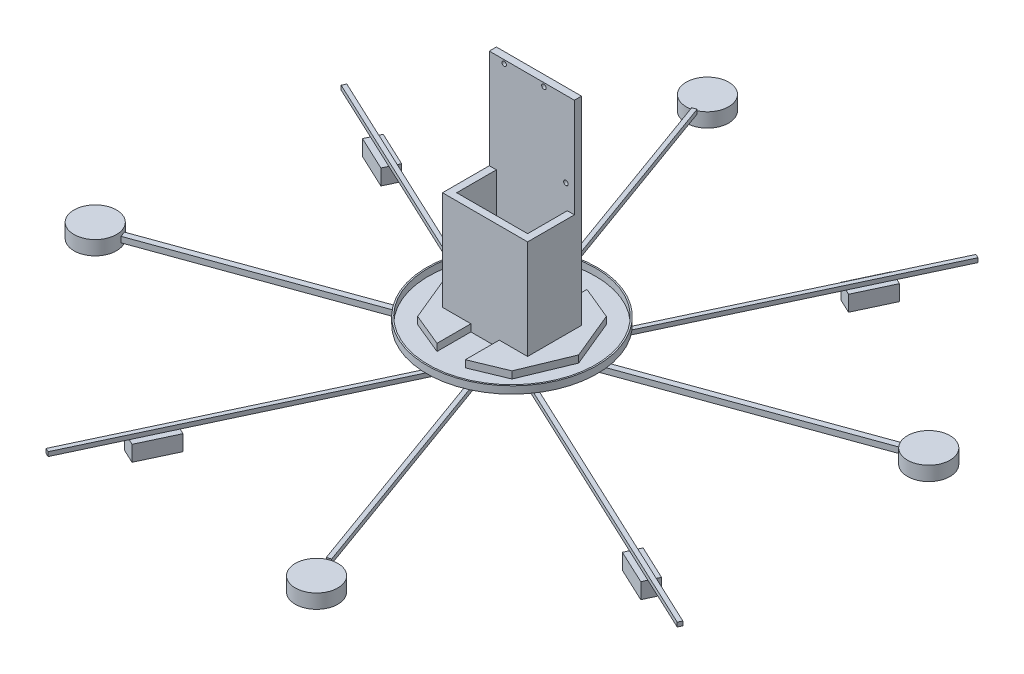
SolidWorks part; units mm, degrees
material "Pieza"
ref_plane "Alzado" through (0, 0, 0) normal (0, 0, 1) x (1, 0, 0)
ref_plane "Planta" through (0, 0, 0) normal (0, 1, 0) x (1, 0, 0)
ref_plane "Vista lateral" through (0, 0, 0) normal (1, 0, 0) x (0, 0, -1)
sketch "Croquis1" plane through (0, 0, 0) normal (0, 1, 0) x (1, 0, 0)
  line L0 (-28, 17) -> (-28, -17)
  line L1 (47.0363, 0) -> (33.2597, 33.2597)
  line L2 (33.2597, 33.2597) -> (0, 47.0363)
  line L3 (0, 47.0363) -> (-33.2597, 33.2597)
  line L4 (-33.2597, 33.2597) -> (-47.0363, 0)
  line L5 (-47.0363, 0) -> (-33.2597, -33.2597)
  line L6 (-33.2597, -33.2597) -> (0, -47.0363)
  line L7 (0, -47.0363) -> (33.2597, -33.2597)
  line L8 (33.2597, -33.2597) -> (47.0363, 0)
  line L9 (-25, 14) -> (25, 14)
  line L10 (-25, 14) -> (-25, -14)
  line L11 (-25, -14) -> (25, -14)
  line L12 (25, 14) -> (25, -14)
  line L13 (-25, 14) -> (25, -14) construction
  line L14 (-25, -14) -> (25, 14) construction
  line L15 (-28, -17) -> (28, -17)
  line L16 (28, 17) -> (28, -17)
  line L17 (-28, 17) -> (28, 17)
  circle A0 centre (0, 0) radius 43.4558 construction
  dimension "D1" = 36
  dimension "D2" = 50
  dimension "D3" = 28
  dimension "D4" = 3
extrude "Saliente-Extruir1" add sketch "Croquis1" along normal blind 5 contours L7 L8 L1 L2 L3 L4 L5 L6 L0 L17 L16 L15 | L17 L0 L15 L16 L9 L12 L11 L10 | L12 L9 L10 L11
sketch "Croquis2" plane through (0, 5, 0) normal (0, 1, 0) x (1, 0, 0)
  line L0 (30, 19) -> (-30, 19)
  line L1 (-30, 19) -> (-30, -19)
  line L2 (-30, -19) -> (30, -19)
  line L3 (30, -19) -> (30, 19)
  line L4 (25, 14) -> (-25, 14)
  line L5 (25, -14) -> (25, 14)
  line L6 (-25, -14) -> (25, -14)
  line L7 (-25, 14) -> (-25, -14)
  line L24 (25, 14) -> (-25, 14)
  line L25 (25, -14) -> (25, 14)
  line L26 (-25, -14) -> (25, -14)
  line L27 (-25, 14) -> (-25, -14)
  dimension "D1" = 5
  dimension "D2" = 0
extrude "Saliente-Extruir2" add sketch "Croquis2" along normal blind 70
sketch "Croquis4" plane through (0, 75, 0) normal (0, 1, 0) x (1, 0, 0)
  line L0 (30, 14) -> (-30, 14)
  line L1 (-30, 19) -> (-30, 14)
  line L2 (30, 19) -> (30, 14)
  line L4 (-30, -19) -> (30, -19)
  line L5 (30, -19) -> (30, 19)
  line L6 (30, 19) -> (-30, 19)
  line L7 (-30, 19) -> (-30, -19)
  line L8 (-30, -19) -> (30, -19) construction
  line L9 (30, -19) -> (30, 19) construction
  line L10 (30, 19) -> (-30, 19)
  line L11 (-30, 19) -> (-30, -19) construction
  dimension "D2" = 5
  dimension "D1" = 0
extrude "Saliente-Extruir4" add sketch "Croquis4" along normal blind 70
sketch "Croquis5" plane through (0, 0, -14) normal (0, 0, 1) x (1, 0, 0)
  line L0 (0, 0) -> (0, 145) construction
  line L1 (-30, 145) -> (30, 145) construction
  line L3 (-26.5, 145) -> (26.5, 145)
  line L4 (-26.5, 145) -> (-26.5, 77)
  line L5 (-26.5, 77) -> (26.5, 77)
  line L6 (26.5, 145) -> (26.5, 77)
  line L7 (-26.5, 145) -> (26.5, 77) construction
  line L8 (-26.5, 77) -> (26.5, 145) construction
  circle A0 centre (-8.5, 142.5) radius 1.59
  circle A1 centre (19.5, 142.5) radius 1.59
  circle A2 centre (-24, 91.5) radius 1.59
  circle A3 centre (-19.5, 142.5) radius 1.59
  circle A4 centre (8.5, 142.5) radius 1.59
  circle A5 centre (24, 91.5) radius 1.59
  point P6 (0, 111)
  point P11 (19.5, 142.5)
  point P12 (-8.5, 142.5)
  point P17 (-24, 91.5)
  dimension "D7" = 3.18
  dimension "D8" = 3.18
  dimension "D11" = 3.18
  dimension "D1" = 53
  dimension "D2" = 68
  dimension "D3" = 65.5
  dimension "D4" = 7
  dimension "D5" = 65.5
  dimension "D6" = 35
  dimension "D9" = 50.5
  dimension "D10" = 14.5
extrude "Cortar-Extruir1" cut sketch "Croquis5" against normal through all contours A3 | A5 | A4
sketch "Croquis6" plane through (0, 5, 0) normal (0, 1, 0) x (1, 0, 0)
  line L0 (0, 47.0363) -> (0, -47.0363) construction
  line L1 (-47.0363, 0) -> (47.0363, 0) construction
  line L2 (30, 19) -> (-30, 19) construction
  line L3 (-10, 49) -> (10, 49)
  line L4 (-10, 49) -> (-10, 19)
  line L5 (-10, 19) -> (10, 19)
  line L6 (10, 49) -> (10, 19)
  line L7 (-10, 49) -> (10, 19) construction
  line L8 (-10, 19) -> (10, 49) construction
  line L9 (-10, -19) -> (10, -19)
  line L10 (10, -49) -> (10, -19)
  line L11 (-10, -49) -> (10, -49)
  line L12 (-10, -49) -> (-10, -19)
  point P8 (0, 34)
  dimension "D1" = 20
  dimension "D2" = 30
extrude "Cortar-Extruir2" cut sketch "Croquis6" against normal through all
sketch "Croquis7" plane through (0, 0, 0) normal (0, -1, 0) x (1, 0, 0)
  circle A0 centre (0, 0) radius 60
  dimension "D1" = 120
extrude "Saliente-Extruir5" add sketch "Croquis7" along normal blind 0.1
sketch "Croquis9" plane through (0, 0, 0) normal (0, 0, 1) x (1, 0, 0)
  line L0 (59, 0) -> (60, 0)
  line L1 (60, 0) -> (-60, 0) construction
  line L2 (60, 0) -> (60, 5)
  line L3 (60, 5) -> (59, 5)
  line L4 (59, 5) -> (59, 0)
  line L5 (60, -0.1) -> (60, 0) construction
  line L6 (0, 0) -> (0, 108.5926) construction
  dimension "D1" = 1
  dimension "D2" = 5
revolve "Revolución1" add sketch "Croquis9" angle 360 about L6
sketch "Croquis10" plane through (0, -0.1, 0) normal (0, -1, 0) x (1, 0, 0)
  line L7 (-21.9638, 41.9554) -> (-45.1977, 14.1362)
  line L8 (-45.1977, 14.1362) -> (-41.9554, -21.9638)
  line L9 (-41.9554, -21.9638) -> (-14.1362, -45.1977)
  line L10 (-14.1362, -45.1977) -> (21.9638, -41.9554)
  line L11 (21.9638, -41.9554) -> (45.1977, -14.1362)
  line L12 (45.1977, -14.1362) -> (41.9554, 21.9638)
  line L13 (41.9554, 21.9638) -> (14.1362, 45.1977)
  line L14 (14.1362, 45.1977) -> (-21.9638, 41.9554)
  circle A0 centre (0, 0) radius 43.752 construction
  dimension "D1" = 36.1
extrude "Saliente-Extruir6" add sketch "Croquis10" along normal blind 0.2
sketch "Croquis11" plane through (0, -0.3, 0) normal (0, -1, 0) x (1, 0, 0)
  line L1 (-18.9219, -0.8699) -> (-12.7647, -13.9949)
  line L2 (-12.7647, -13.9949) -> (0.8699, -18.9219)
  line L3 (0.8699, -18.9219) -> (13.9949, -12.7647)
  line L4 (13.9949, -12.7647) -> (18.9219, 0.8699)
  line L5 (18.9219, 0.8699) -> (12.7647, 13.9949)
  line L6 (12.7647, 13.9949) -> (-0.8699, 18.9219)
  line L7 (-0.8699, 18.9219) -> (-13.9949, 12.7647)
  line L8 (-13.9949, 12.7647) -> (-18.9219, -0.8699)
  circle A0 centre (0, 0) radius 17.5 construction
  dimension "D2" = 17.5
extrude "Saliente-Extruir7" add sketch "Croquis11" along normal blind 22.1
sketch "Croquis12" plane through (5.9474, 0, 16.4584) normal (0.3399, 0, 0.9405) x (0.9405, 0, -0.3399)
  line L0 (7.2487, -22.4) -> (-7.2487, -22.4) construction
  line L1 (-1.6681, -5.4) -> (1.3319, -5.4)
  line L2 (-1.6681, -5.4) -> (-1.6681, -8.4)
  line L3 (-1.6681, -8.4) -> (1.3319, -8.4)
  line L4 (1.3319, -5.4) -> (1.3319, -8.4)
  dimension "D1" = 14
  dimension "D2" = 3
extrude "Saliente-Extruir8" add sketch "Croquis12" along normal blind 197
sketch "Croquis13" plane through (-5.9474, 0, -16.4584) normal (-0.3399, 0, -0.9405) x (-0.9405, 0, 0.3399)
  line L0 (-1.3319, -5.4) -> (1.6681, -5.4) construction
  line L1 (1.6681, -5.4) -> (1.6681, -8.4) construction
  line L2 (1.6681, -8.4) -> (-1.3319, -8.4) construction
  line L3 (-1.3319, -8.4) -> (-1.3319, -5.4) construction
  line L4 (-1.3319, -5.4) -> (1.6681, -5.4)
  line L5 (1.6681, -5.4) -> (1.6681, -8.4)
  line L6 (1.6681, -8.4) -> (-1.3319, -8.4)
  line L7 (-1.3319, -8.4) -> (-1.3319, -5.4)
extrude "Saliente-Extruir9" add sketch "Croquis13" along normal blind 197
sketch "Croquis14" plane through (-16.4584, 0, 5.9474) normal (-0.9405, 0, 0.3399) x (0.3399, 0, 0.9405)
  line L0 (7.2487, -22.4) -> (-7.2487, -22.4) construction
  line L1 (-2.2487, -9.4) -> (1.7513, -9.4)
  line L2 (-2.2487, -9.4) -> (-2.2487, -13.4)
  line L3 (-2.2487, -13.4) -> (1.7513, -13.4)
  line L4 (1.7513, -9.4) -> (1.7513, -13.4)
  line L5 (-7.2487, -22.4) -> (-7.2487, -0.3) construction
  dimension "D1" = 9
  dimension "D2" = 4
  dimension "D3" = 4
  dimension "D4" = 5
extrude "Saliente-Extruir10" add sketch "Croquis14" along normal blind 197
sketch "Croquis15" plane through (16.4584, 0, -5.9474) normal (0.9405, 0, -0.3399) x (-0.3399, 0, -0.9405)
  line L0 (2.2487, -9.4) -> (2.2487, -13.4) construction
  line L1 (2.2487, -13.4) -> (-1.7513, -13.4) construction
  line L2 (-1.7513, -9.4) -> (2.2487, -9.4) construction
  line L3 (-1.7513, -13.4) -> (-1.7513, -9.4) construction
  line L12 (2.2487, -9.4) -> (2.2487, -13.4)
  line L13 (2.2487, -13.4) -> (-1.7513, -13.4)
  line L14 (-1.7513, -9.4) -> (2.2487, -9.4)
  line L15 (-1.7513, -13.4) -> (-1.7513, -9.4)
extrude "Saliente-Extruir12" add sketch "Croquis15" along normal blind 197 contours L14 L12 L13 L15
ref_plane "Plano1" through (0, -6.4, 0) normal (0, 1, 0) x (1, 0, 0)
sketch "Croquis17" plane through (0, -6.4, 0) normal (0, 1, 0) x (1, 0, 0)
  line L0 (-201.1377, -74.545) -> (-202.4971, -70.7831) construction
  line L1 (104.0732, -288.0051) -> (-104.0732, 288.0051) construction
  circle A0 centre (-215.8297, -78.0242) radius 15
  circle A1 centre (-78.0242, 215.8297) radius 15
  circle A2 centre (215.8297, 78.0242) radius 15
  circle A3 centre (78.0242, -215.8297) radius 15
  point P8 (0, 0)
  point P17 (0, 0)
  dimension "D1" = 4
  dimension "D2" = 30
extrude "Saliente-Extruir13" add sketch "Croquis17" against normal blind 10 separate body
sketch "Croquis18" plane through (7.4324, 0, -15.8433) normal (0.4247, 0, -0.9053) x (-0.9053, 0, -0.4247)
  line L0 (7.2487, -22.4) -> (-7.2487, -22.4) construction
  line L1 (1.5, -20.4) -> (-1.5, -20.4)
  line L2 (1.5, -20.4) -> (1.5, -17.4)
  line L3 (1.5, -17.4) -> (-1.5, -17.4)
  line L4 (-1.5, -20.4) -> (-1.5, -17.4)
  line L5 (1.5, -20.4) -> (-1.5, -17.4) construction
  line L6 (1.5, -17.4) -> (-1.5, -20.4) construction
  point P0 (0, -18.9)
  point P7 (0, -22.4)
  dimension "D1" = 2
  dimension "D2" = 3
  dimension "D3" = 3
extrude "Saliente-Extruir14" add sketch "Croquis18" along normal blind 229
sketch "Croquis19" plane through (-7.4324, 0, 15.8433) normal (-0.4247, 0, 0.9053) x (0.9053, 0, 0.4247)
  line L0 (1.5, -20.4) -> (-1.5, -20.4) construction
  line L1 (1.5, -17.4) -> (1.5, -20.4) construction
  line L2 (-1.5, -17.4) -> (1.5, -17.4) construction
  line L3 (-1.5, -20.4) -> (-1.5, -17.4) construction
  line L12 (1.5, -20.4) -> (-1.5, -20.4)
  line L13 (1.5, -17.4) -> (1.5, -20.4)
  line L14 (-1.5, -17.4) -> (1.5, -17.4)
  line L15 (-1.5, -20.4) -> (-1.5, -17.4)
extrude "Saliente-Extruir15" add sketch "Croquis19" along normal blind 229
sketch "Croquis20" plane through (15.8433, 0, 7.4324) normal (0.9053, 0, 0.4247) x (0.4247, 0, -0.9053)
  line L0 (7.2487, -22.4) -> (-7.2487, -22.4) construction
  line L2 (1.5, -20.4) -> (-1.5, -20.4)
  line L3 (1.5, -20.4) -> (1.5, -17.4)
  line L4 (1.5, -17.4) -> (-1.5, -17.4)
  line L5 (-1.5, -20.4) -> (-1.5, -17.4)
  line L6 (1.5, -20.4) -> (-1.5, -17.4) construction
  line L7 (1.5, -17.4) -> (-1.5, -20.4) construction
  point P0 (0, -22.4)
  point P1 (0, -18.9)
  dimension "D1" = 2
  dimension "D2" = 3
  dimension "D3" = 3
extrude "Saliente-Extruir16" add sketch "Croquis20" along normal blind 229
sketch "Croquis21" plane through (-15.8433, 0, -7.4324) normal (-0.9053, 0, -0.4247) x (-0.4247, 0, 0.9053)
  line L0 (1.5, -17.4) -> (1.5, -20.4) construction
  line L1 (-1.5, -17.4) -> (1.5, -17.4) construction
  line L2 (1.5, -20.4) -> (-1.5, -20.4) construction
  line L3 (-1.5, -20.4) -> (-1.5, -17.4) construction
  line L4 (1.5, -17.4) -> (1.5, -20.4)
  line L5 (-1.5, -17.4) -> (1.5, -17.4)
  line L6 (1.5, -20.4) -> (-1.5, -20.4)
  line L7 (-1.5, -20.4) -> (-1.5, -17.4)
extrude "Saliente-Extruir17" add sketch "Croquis21" along normal blind 229
sketch "Croquis22" plane through (0, -20.4, 0) normal (0, -1, 0) x (1, 0, 0)
  line L0 (106.0487, -222.5268) -> (103.3327, -223.8009) construction
  line L7 (91.1998, -181.9962) -> (81.2412, -186.668)
  line L11 (81.2412, -186.668) -> (69.774, -162.2241)
  line L12 (69.774, -162.2241) -> (79.7327, -157.5523)
  line L14 (79.7327, -157.5523) -> (91.1998, -181.9962)
  line L15 (106.0487, -222.5268) -> (8.7904, -15.2062) construction
  line L16 (103.3327, -223.8009) -> (6.0744, -16.4803) construction
  line L17 (149.0238, 412.3982) -> (-149.0238, -412.3982) construction
  line L18 (-157.5523, -79.7327) -> (-181.9962, -91.1998)
  line L19 (-181.9962, -91.1998) -> (-186.668, -81.2412)
  line L20 (-186.668, -81.2412) -> (-162.2241, -69.774)
  line L21 (-162.2241, -69.774) -> (-157.5523, -79.7327)
  line L22 (-79.7327, 157.5523) -> (-91.1998, 181.9962)
  line L23 (-91.1998, 181.9962) -> (-81.2412, 186.668)
  line L24 (-81.2412, 186.668) -> (-69.774, 162.2241)
  line L25 (-69.774, 162.2241) -> (-79.7327, 157.5523)
  line L26 (157.5523, 79.7327) -> (181.9962, 91.1998)
  line L27 (181.9962, 91.1998) -> (186.668, 81.2412)
  line L28 (186.668, 81.2412) -> (162.2241, 69.774)
  line L29 (162.2241, 69.774) -> (157.5523, 79.7327)
  point P0 (104.6907, -223.1639)
  point P15 (0, 0)
  point P30 (0, 0)
  dimension "D1" = 70
  dimension "D2" = 27
  dimension "D3" = 11
  dimension "D4" = 4
extrude "Saliente-Extruir18" add sketch "Croquis22" along normal blind 11
ref_plane "Plano2" through (-0.1581, 0, 0.0571) normal (-0.9405, 0, 0.3399) x (0.3399, 0, 0.9405)
ref_plane "Plano3" through (-0.0845, 0, -0.2339) normal (0.3399, 0, 0.9405) x (0.9405, 0, -0.3399)
